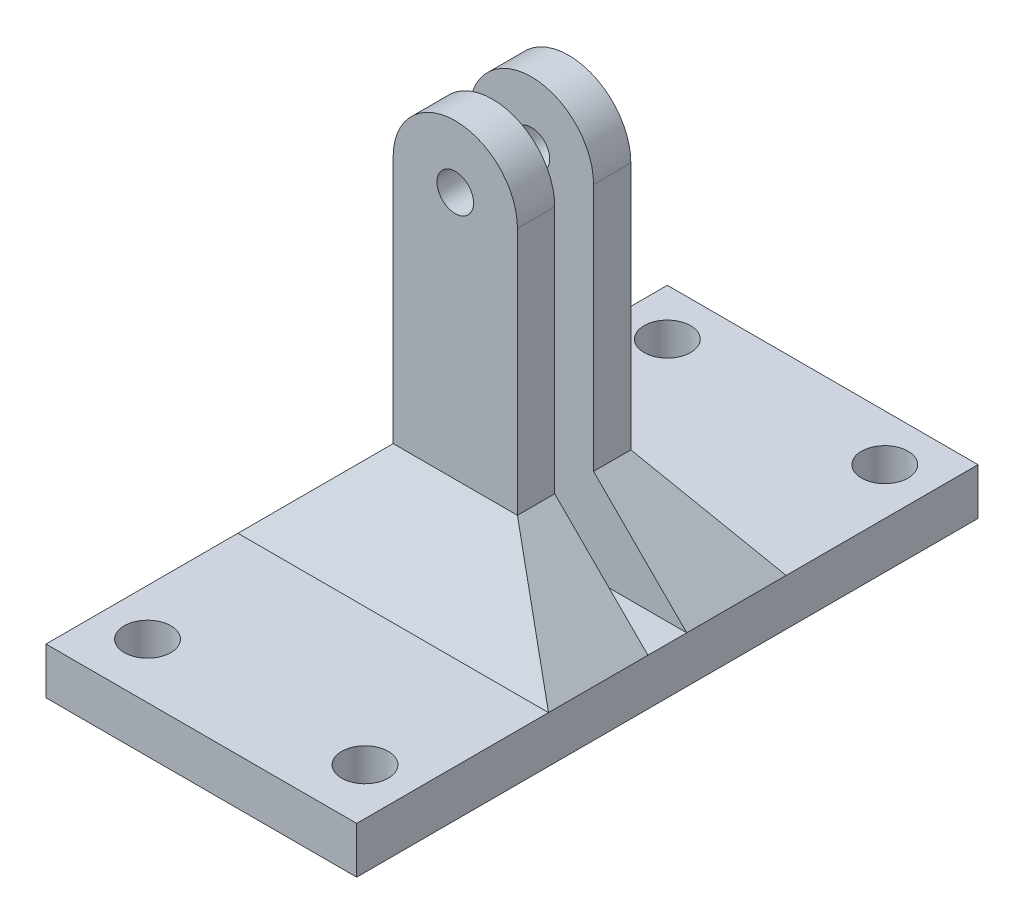
SolidWorks part; units mm, degrees
ref_plane "Front Plane" through (0, 0, 0) normal (0, 0, 1) x (1, 0, 0)
ref_plane "Top Plane" through (0, 0, 0) normal (0, 1, 0) x (1, 0, 0)
ref_plane "Right Plane" through (0, 0, 0) normal (1, 0, 0) x (0, 0, -1)
sketch "Sketch1" plane through (0, 0, 0) normal (0, 1, 0) x (1, 0, 0)
  line L1 (-10, -20) -> (10, -20)
  line L2 (-10, -20) -> (-10, 20)
  line L3 (-10, 20) -> (10, 20)
  line L4 (10, -20) -> (10, 20)
  line L5 (-10, -20) -> (10, 20) construction
  line L6 (-10, 20) -> (10, -20) construction
  point P0 (0, 0)
  dimension "D1" = 40
  dimension "D2" = 20
extrude "Boss-Extrude1" add sketch "Sketch1" along normal blind 3
sketch "Sketch2" plane through (0, 3, 0) normal (0, 1, 0) x (1, 0, 0)
  line L0 (-10, 20) -> (-10, -20) construction
  line L5 (10, -20) -> (10, 20) construction
  line L6 (10, 20) -> (-10, 20) construction
  line L7 (-10, 7.65) -> (10, 7.65)
  line L8 (-10, 7.65) -> (-10, 1.25)
  line L9 (-10, 1.25) -> (10, 1.25)
  line L10 (10, 7.65) -> (10, 1.25)
  dimension "D2" = 6.4
  dimension "D4" = 12.35
ref_plane "Plane1" through (0, 9, 0) normal (0, 1, 0) x (1, 0, 0)
sketch "Sketch3" plane through (0, 9, 0) normal (0, 1, 0) x (1, 0, 0)
  line L12 (-10, 7.65) -> (-10, 1.25) construction
  line L13 (-4, 3.65) -> (4, 3.65)
  line L14 (-4, 3.65) -> (-4, 1.25)
  line L15 (-4, 1.25) -> (4, 1.25)
  line L16 (4, 3.65) -> (4, 1.25)
  line L17 (-10, 1.25) -> (10, 1.25) construction
  line L18 (-10, 0) -> (10, 0) construction
  line L19 (-10, 20) -> (-10, -20) construction
  line L20 (10, -20) -> (10, 20) construction
  point P4 (0, 3.65)
  dimension "D1" = 2.4
  dimension "D2" = 8
  dimension "D3" = 10
loft "Loft3" add profiles "Sketch2", "Sketch3"
ref_plane "Plane2" through (0, 0, 0) normal (0, 0, -1) x (-1, 0, 0)
mirror "Mirror1" about plane through (0, 0, 0) normal (0, 0, -1) of "Loft3"
sketch "Sketch4" plane through (0, 9, 0) normal (0, 1, 0) x (1, 0, 0)
  line L1 (-4, 1.25) -> (4, 1.25)
  line L2 (-4, 1.25) -> (-4, 3.65)
  line L3 (-4, 3.65) -> (4, 3.65)
  line L4 (4, 1.25) -> (4, 3.65)
  line L5 (-4, -1.25) -> (4, -1.25)
  line L6 (-4, -1.25) -> (-4, -3.65)
  line L7 (-4, -3.65) -> (4, -3.65)
  line L8 (4, -1.25) -> (4, -3.65)
extrude "Boss-Extrude2" add sketch "Sketch4" along normal blind 20
sketch "Sketch5" plane through (0, 0, 3.65) normal (0, 0, 1) x (1, 0, 0)
  line L0 (-4, 29) -> (4, 29) construction
  line L1 (-4, 25) -> (-4, 29)
  line L2 (-4, 29) -> (4, 29)
  line L3 (4, 29) -> (4, 25)
  circle A0 centre (0, 25) radius 1.1787
  arc A1 (4, 25) -> (-4, 25) centre (0, 25) ccw
  line M3 (4, 9) -> (4, 29)
  line M4 (4, 29) -> (-4, 29)
  line M5 (-4, 29) -> (-4, 9)
  dimension "D1" = 8
extrude "Cut-Extrude1" cut sketch "Sketch5" against normal up to surface (7.3 mm away) contours A1 L2 M5 | A1 M3 M4 | A0 up to face at (1, 24, -3.65)
sketch "Sketch6" plane through (0, 3, 0) normal (0, 1, 0) x (1, 0, 0)
  line L0 (10, 20) -> (-10, 20) construction
  line L1 (10, 7.65) -> (10, 20) construction
  circle A0 centre (7, 17) radius 1.5
  circle A1 centre (-7, 17) radius 1.5
  circle A2 centre (7, -16.4636) radius 1.5
  circle A3 centre (-7, -16.4636) radius 1.5
  dimension "D1" = 3
  dimension "D2" = 3
  dimension "D3" = 3
  dimension "D4" = 14
extrude "Cut-Extrude2" cut sketch "Sketch6" against normal up to surface (3 mm away) up to face at (0, 0, 0)
